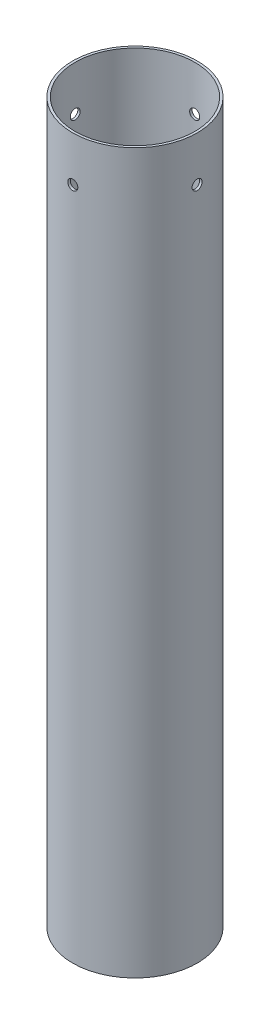
SolidWorks part; units mm, degrees
material "S-Glass Fiber"
ref_plane "Front Plane" through (0, 0, 0) normal (0, 0, 1) x (1, 0, 0)
ref_plane "Top Plane" through (0, 0, 0) normal (0, 1, 0) x (1, 0, 0)
ref_plane "Right Plane" through (0, 0, 0) normal (1, 0, 0) x (0, 0, -1)
sketch "Sketch1" plane through (0, 0, 0) normal (0, 1, 0) x (1, 0, 0)
  circle A0 centre (0, 0) radius 39.624
  circle A1 centre (0, 0) radius 38.1
  dimension "D1" = 79.248
  dimension "D2" = 76.2
extrude "Boss-Extrude1" add sketch "Sketch1" along normal blind 457.2 contours A1 | A0
sketch "Sketch2" plane through (0, 0, 0) normal (0, 0, 1) x (1, 0, 0)
  line L0 (39.624, 457.2) -> (-39.624, 457.2) construction
  circle A0 centre (0, 428.625) radius 3.175
  point P5 (0, 0)
  dimension "D2" = 6.35
  dimension "D1" = 28.575
extrude "Cut-Extrude1" cut sketch "Sketch2" along normal through all
pattern_circular "CirPattern1" count 4 over 360 about axis through (0, 457.2, 0) along (0, -1, 0) of "Cut-Extrude1"
